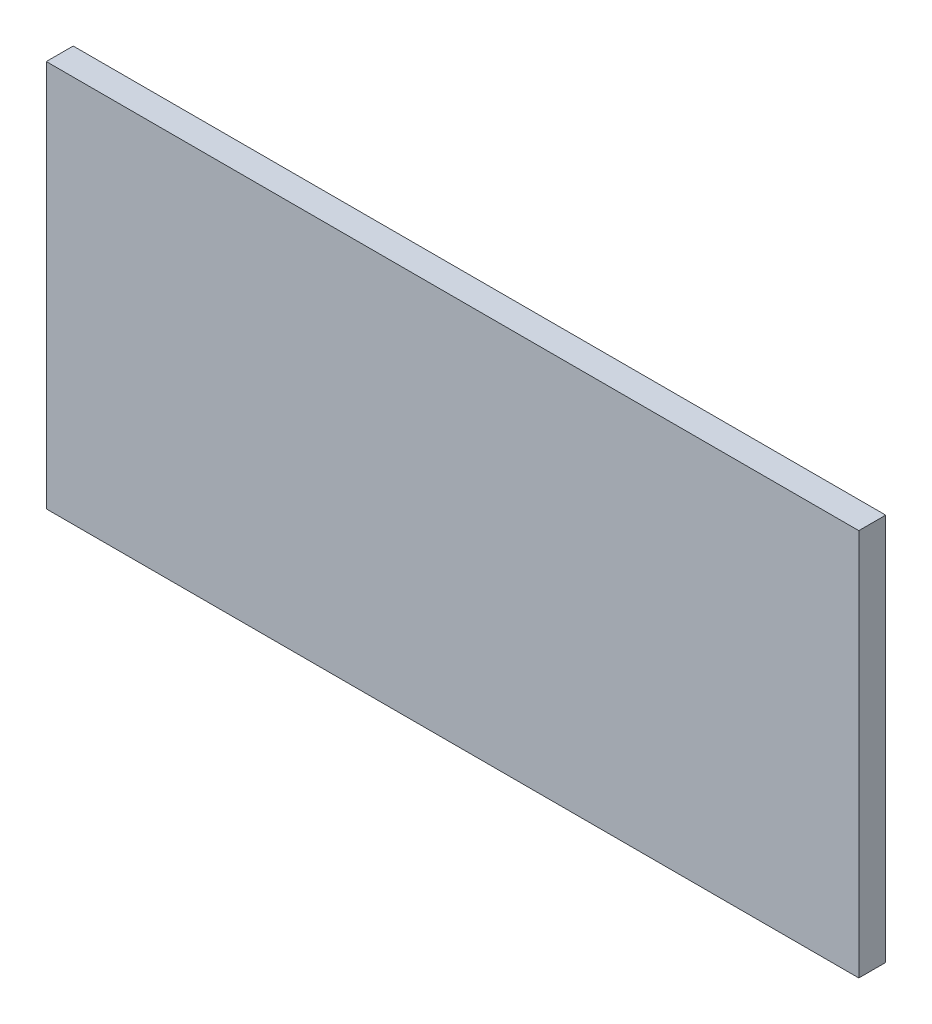
SolidWorks part; units mm, degrees
ref_plane "Front Plane" through (0, 0, 0) normal (0, 0, 1) x (1, 0, 0)
ref_plane "Top Plane" through (0, 0, 0) normal (0, 1, 0) x (1, 0, 0)
ref_plane "Right Plane" through (0, 0, 0) normal (1, 0, 0) x (0, 0, -1)
sketch "Sketch1" plane through (0, 0, 0) normal (0, 0, 1) x (1, 0, 0)
  line L1 (-75.5, 36) -> (75.5, 36)
  line L2 (-75.5, 36) -> (-75.5, -36)
  line L3 (-75.5, -36) -> (75.5, -36)
  line L4 (75.5, 36) -> (75.5, -36)
  dimension "D1" = 151
  dimension "D2" = 75.5
  dimension "D3" = 72
  dimension "D4" = 36
extrude "Boss-Extrude1" add sketch "Sketch1" along normal blind 5
